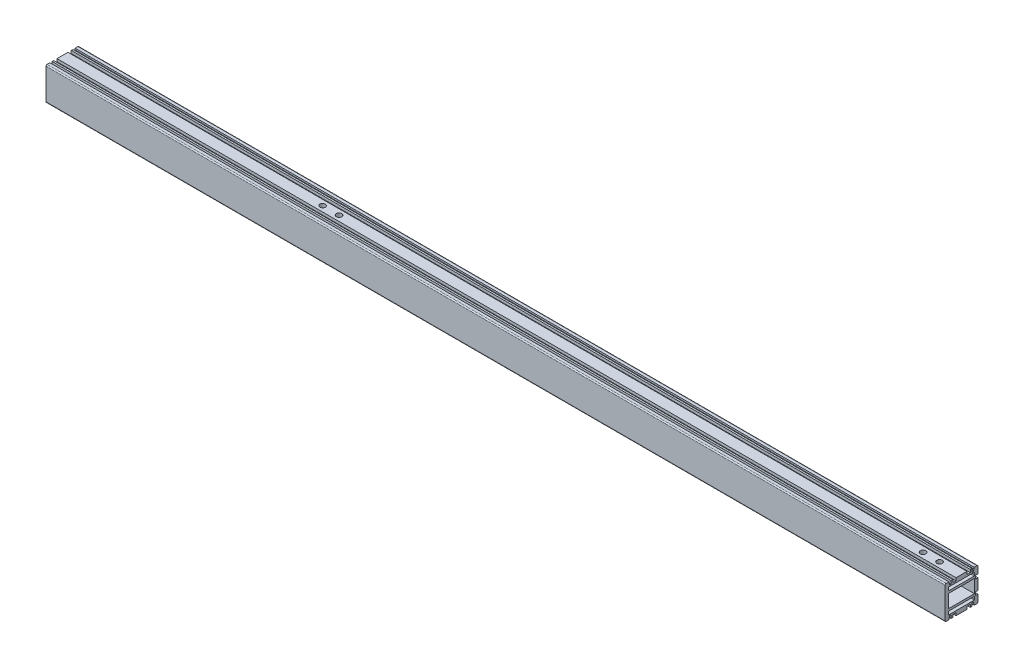
SolidWorks part; units mm, degrees
ref_plane "前视基准面" through (0, 0, 0) normal (0, 0, 1) x (1, 0, 0)
ref_plane "上视基准面" through (0, 0, 0) normal (0, 1, 0) x (1, 0, 0)
ref_plane "右视基准面" through (0, 0, 0) normal (1, 0, 0) x (0, 0, -1)
sketch "草图1" plane through (0, 0, 0) normal (1, 0, 0) x (0, 0, -1)
  line L0 (-15, 15) -> (15, -15) construction
  line L1 (-14, 15) -> (-11.5, 15)
  line L2 (-15, 14) -> (-15, -14)
  line L3 (-14, -15) -> (-11.5, -15)
  line L4 (15, 14) -> (15, 8)
  line L5 (15, 15) -> (-15, -15) construction
  line L6 (-11.5, 15) -> (-11.5, 13.5)
  line L7 (-11.5, 13.5) -> (-11.4, 13.5)
  line L8 (-11, 13.1) -> (-11, 12)
  line L9 (-11, 12) -> (-9.5, 12)
  line L10 (-9.5, 12) -> (-9.5, 15)
  line L11 (-9.5, 15) -> (-8, 15)
  line L12 (-8, 15) -> (-8, 12.5)
  line L13 (-8, 12.5) -> (-5, 12.5)
  line L14 (-5, 12.5) -> (-5, 15)
  line L15 (-5, 15) -> (5, 15)
  line L16 (0, 21.5201) -> (0, -18.309) construction
  line L17 (0, 55) -> (0, -55) construction
  line L18 (5, 12.5) -> (5, 15)
  line L19 (8, 12.5) -> (5, 12.5)
  line L20 (8, 15) -> (8, 12.5)
  line L21 (9.5, 15) -> (8, 15)
  line L22 (9.5, 12) -> (9.5, 15)
  line L23 (11, 12) -> (9.5, 12)
  line L24 (11, 13.1) -> (11, 12)
  line L25 (11.5, 13.5) -> (11.4, 13.5)
  line L26 (11.5, 15) -> (11.5, 13.5)
  line L27 (8, 15) -> (9.5, 15)
  line L28 (11.5, 15) -> (14, 15)
  line L29 (-19.8303, 0) -> (22.13, 0) construction
  line L30 (55, 0) -> (-55, 0) construction
  line L31 (8, -15) -> (9.5, -15)
  line L32 (11.5, -15) -> (11.5, -13.5)
  line L33 (11.5, -13.5) -> (11.4, -13.5)
  line L34 (11, -13.1) -> (11, -12)
  line L35 (11, -12) -> (9.5, -12)
  line L36 (9.5, -12) -> (9.5, -15)
  line L37 (9.5, -15) -> (8, -15)
  line L38 (8, -15) -> (8, -12.5)
  line L39 (8, -12.5) -> (5, -12.5)
  line L40 (5, -12.5) -> (5, -15)
  line L41 (-5, -15) -> (5, -15)
  line L42 (-5, -12.5) -> (-5, -15)
  line L43 (-8, -12.5) -> (-5, -12.5)
  line L44 (-8, -15) -> (-8, -12.5)
  line L45 (-9.5, -15) -> (-8, -15)
  line L46 (-9.5, -12) -> (-9.5, -15)
  line L47 (-11, -12) -> (-9.5, -12)
  line L48 (-11, -13.1) -> (-11, -12)
  line L49 (-11.5, -13.5) -> (-11.4, -13.5)
  line L50 (-11.5, -15) -> (-11.5, -13.5)
  line L51 (-9.5, -15) -> (-8, -15)
  line L52 (-5, -15) -> (5, -15)
  line L53 (8, -15) -> (9.5, -15)
  line L54 (11.5, -15) -> (14, -15)
  line L55 (15, 8) -> (12.5, 8)
  line L56 (12.5, 8) -> (12.5, 5)
  line L57 (12.5, 5) -> (15, 5)
  line L58 (12.5, -5) -> (15, -5)
  line L59 (12.5, -8) -> (12.5, -5)
  line L60 (15, -8) -> (12.5, -8)
  line L61 (15, 5) -> (15, -5)
  line L62 (15, -8) -> (15, -14)
  line L63 (12, -10.5) -> (12, -8.5)
  line L64 (-11.5, 11) -> (11.5, 11)
  line L65 (-12, 10.5) -> (-12, 8.5)
  line L66 (-11.5, 8) -> (11.5, 8)
  line L67 (12, 10.5) -> (12, 8.5)
  line L68 (-11.5, -8) -> (11.5, -8)
  line L69 (-12, -10.5) -> (-12, -8.5)
  line L70 (-11.5, -11) -> (11.5, -11)
  line L72 (-11.75, 6) -> (11.75, 6)
  line L73 (-11.75, 6) -> (-11.75, -6)
  line L74 (-11.75, -6) -> (11.75, -6)
  line L75 (11.75, 6) -> (11.75, -6)
  arc A0 (12, 8.5) -> (11.5, 8) centre (11.5, 8.5) cw
  arc A1 (11.5, 11) -> (12, 10.5) centre (11.5, 10.5) cw
  arc A2 (-11.5, 11) -> (-12, 10.5) centre (-11.5, 10.5) ccw
  arc A3 (-11.5, 8) -> (-12, 8.5) centre (-11.5, 8.5) cw
  arc A4 (-11, -13.1) -> (-11.4, -13.5) centre (-11.4, -13.1) cw
  arc A5 (11.4, -13.5) -> (11, -13.1) centre (11.4, -13.1) cw
  arc A6 (11.4, 13.5) -> (11, 13.1) centre (11.4, 13.1) ccw
  arc A7 (-11, 13.1) -> (-11.4, 13.5) centre (-11.4, 13.1) ccw
  arc A8 (-11.5, -8) -> (-12, -8.5) centre (-11.5, -8.5) ccw
  arc A9 (-11.5, -11) -> (-12, -10.5) centre (-11.5, -10.5) cw
  arc A10 (11.5, -11) -> (12, -10.5) centre (11.5, -10.5) ccw
  arc A11 (12, -8.5) -> (11.5, -8) centre (11.5, -8.5) ccw
  arc A12 (14, 15) -> (15, 14) centre (14, 14) cw
  arc A13 (14, -15) -> (15, -14) centre (14, -14) ccw
  arc A14 (-15, -14) -> (-14, -15) centre (-14, -14) ccw
  arc A15 (-15, 14) -> (-14, 15) centre (-14, 14) cw
  point P69 (12, 11)
  point P72 (-12, 11)
  point P77 (-11, -13.5)
  point P80 (11, -13.5)
  point P83 (11, 13.5)
  point P86 (-11, 13.5)
  point P99 (-12, -11)
  point P100 (12, -11)
  dimension "D17" = 0.5
  dimension "D18" = 0.4
  dimension "D21" = 1
  dimension "D1" = 3.5
  dimension "D2" = 1.5
  dimension "D3" = 0.5
  dimension "D4" = 1.5
  dimension "D5" = 3
  dimension "D6" = 30
  dimension "D7" = 30
  dimension "D8" = 1.5
  dimension "D9" = 2.5
  dimension "D10" = 3
  dimension "D11" = 2.5
  dimension "D12" = 7
  dimension "D13" = 3
  dimension "D14" = 4
  dimension "D15" = 3
  dimension "D16" = 24
  dimension "D19" = 23.5
  dimension "D20" = 12
extrude "凸台-拉伸1" add sketch "草图1" along normal mid plane 819 contours A15 L2 A14 L3 L50 L49 A4 L48 L47 L46 L45 L44 L43 L42 L41 L40 L39 L38 L31 L36 L35 L34 A5 L33 L32 L54 A13 L62 L60 L59 L58 L61 L57 L56 L55 L4 A12 L28 L26 L25 A6 L24 L23 L22 L21 L20 L19 L18 L15 L14 L13
hole_wizard "M6 螺纹孔1" positions "草图3" profile "草图2" tap size "M6" standard "GB"
sketch "草图3" plane through (0, -15, 0) normal (0, -1, 0) x (1, 0, 0)
  line L0 (409.5, 5) -> (409.5, -5) construction
  line L1 (409.5, 15) -> (-409.5, 15) construction
  point P0 (389.5, 0)
  point P1 (374.5, 0)
  point P4 (-192.5, 0)
  point P7 (-207.5, 0)
  point P10 (-277.5, 0)
  point P13 (-292.5, 0)
  point P16 (-374.5, 0)
  point P19 (-389.5, 0)
  dimension "D1" = 20
  dimension "D2" = 15
sketch "草图2" plane through (389.5, -15, 0) normal (1, 0, 0) x (0, 0, -1)
  line L0 (0, 0) -> (0, 16.5022)
  line L1 (0, 16.5022) -> (2.5, 15)
  line L2 (2.5, 15) -> (2.5, 0)
  line L5 (2.5, 0) -> (0, 0)
  line L10 (0, 16.5022) -> (-2.5, 15) construction
  line L11 (0, -6.35) -> (0, 107.95) construction
  dimension "螺纹孔钻头直径" = 5
  dimension "螺纹孔钻头深度" = 15
  dimension "导头角度" = 118
cosmetic thread "孔螺蚊线1" parameters "D1"=9, "D2"=6
cosmetic thread "孔螺蚊线2" parameters "D1"=9, "D2"=6
cosmetic thread "孔螺蚊线3" parameters "D1"=9, "D2"=6
cosmetic thread "孔螺蚊线4" parameters "D1"=9, "D2"=6
cosmetic thread "孔螺蚊线5" parameters "D1"=9, "D2"=6
cosmetic thread "孔螺蚊线6" parameters "D1"=9, "D2"=6
cosmetic thread "孔螺蚊线7" parameters "D1"=9, "D2"=6
cosmetic thread "孔螺蚊线8" parameters "D1"=9, "D2"=6
hole_wizard "M6 螺纹孔2" positions "草图5" profile "草图4" tap size "M6" standard "GB"
sketch "草图5" plane through (0, 0, -15) normal (0, 0, -1) x (-1, 0, 0)
  line L0 (409.5, 5) -> (409.5, -5) construction
  line L1 (-409.5, 15) -> (409.5, 15) construction
  point P0 (389.5, 0)
  point P1 (374.5, 0)
  point P4 (292.5, 0)
  point P7 (277.5, 0)
  point P10 (207.5, 0)
  point P13 (192.5, 0)
  dimension "D1" = 20
  dimension "D2" = 15
sketch "草图4" plane through (-389.5, 0, -15) normal (1, 0, 0) x (0, 1, 0)
  line L0 (0, 0) -> (0, 16.5022)
  line L1 (0, 16.5022) -> (2.5, 15)
  line L2 (2.5, 15) -> (2.5, 0)
  line L5 (2.5, 0) -> (0, 0)
  line L10 (0, 16.5022) -> (-2.5, 15) construction
  line L11 (0, -6.35) -> (0, 107.95) construction
  dimension "螺纹孔钻头直径" = 5
  dimension "螺纹孔钻头深度" = 15
  dimension "导头角度" = 118
cosmetic thread "孔螺蚊线9" parameters "D1"=3.25, "D2"=6
cosmetic thread "孔螺蚊线10" parameters "D1"=3.25, "D2"=6
cosmetic thread "孔螺蚊线11" parameters "D1"=3.25, "D2"=6
cosmetic thread "孔螺蚊线12" parameters "D1"=3.25, "D2"=6
cosmetic thread "孔螺蚊线13" parameters "D1"=3.25, "D2"=6
cosmetic thread "孔螺蚊线14" parameters "D1"=3.25, "D2"=6
hole_wizard "M6 螺纹孔3" positions "草图7" profile "草图6" tap size "M6" standard "GB"
sketch "草图7" plane through (0, 15, 0) normal (0, 1, 0) x (-1, 0, 0)
  line L0 (192.5, 5) -> (192.5, -5) construction
  line L1 (-409.5, -15) -> (409.5, -15) construction
  point P0 (172.5, 0)
  point P1 (157.5, 0)
  point P4 (-374.5, 0)
  point P7 (-389.5, 0)
  dimension "D1" = 20
  dimension "D2" = 15
sketch "草图6" plane through (-172.5, 15, 0) normal (1, 0, 0) x (0, 0, 1)
  line L0 (0, 0) -> (0, 16.5022)
  line L1 (0, 16.5022) -> (2.5, 15)
  line L2 (2.5, 15) -> (2.5, 0)
  line L5 (2.5, 0) -> (0, 0)
  line L10 (0, 16.5022) -> (-2.5, 15) construction
  line L11 (0, -6.35) -> (0, 107.95) construction
  dimension "螺纹孔钻头直径" = 5
  dimension "螺纹孔钻头深度" = 15
  dimension "导头角度" = 118
cosmetic thread "孔螺蚊线15" parameters "D1"=9, "D2"=6
cosmetic thread "孔螺蚊线16" parameters "D1"=9, "D2"=6
cosmetic thread "孔螺蚊线17" parameters "D1"=9, "D2"=6
cosmetic thread "孔螺蚊线18" parameters "D1"=9, "D2"=6
